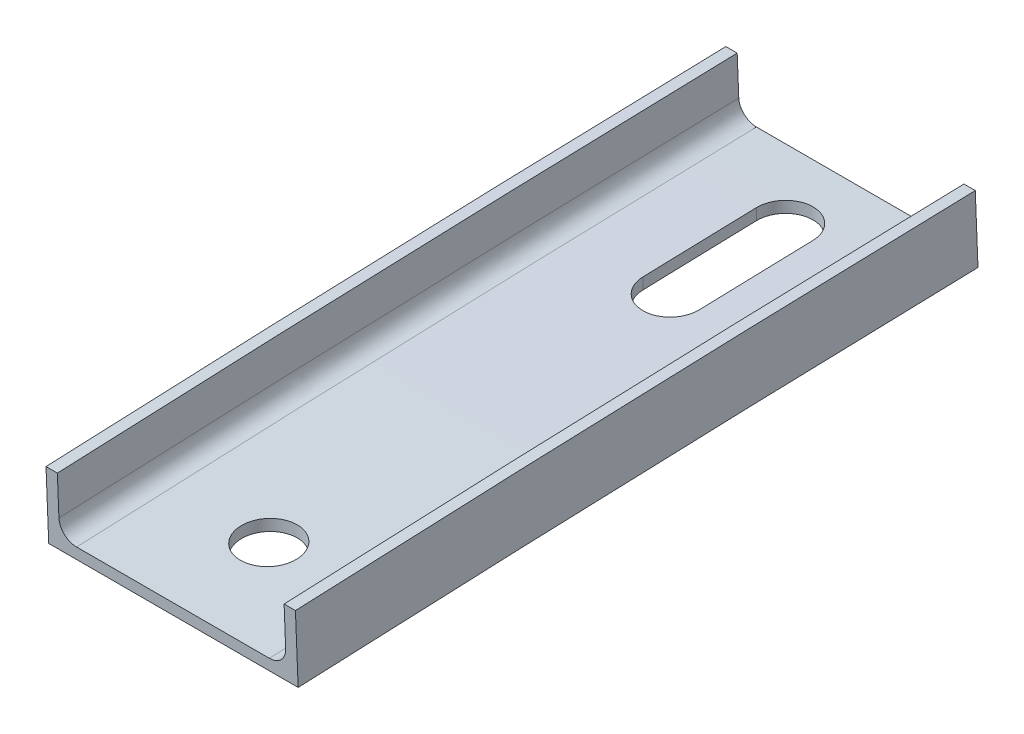
SolidWorks part; units mm, degrees
ref_plane "Front Plane" through (0, 0, 0) normal (0, 0, 1) x (1, 0, 0)
ref_plane "Top Plane" through (0, 0, 0) normal (0, 1, 0) x (1, 0, 0)
ref_plane "Right Plane" through (0, 0, 0) normal (1, 0, 0) x (0, 0, -1)
sketch "Sketch1" plane through (0, 0, 0) normal (0, 0, 1) x (1, 0, 0)
  line L0 (-17, 0) -> (17, 0)
  line L1 (-20, 3) -> (-20, 10)
  line L2 (-20, 10) -> (-22, 10)
  line L3 (-22, 10) -> (-22, -2)
  line L4 (-22, -2) -> (22, -2)
  line L5 (22, -2) -> (22, 10)
  line L6 (22, 10) -> (20, 10)
  line L7 (20, 10) -> (20, 3)
  arc A0 (17, 0) -> (20, 3) centre (17, 3) ccw
  arc A1 (-17, 0) -> (-20, 3) centre (-17, 3) cw
  point P4 (0, 0)
  point P12 (20, 0)
  point P15 (-20, 0)
  dimension "D4" = 3
  dimension "D1" = 2
  dimension "D2" = 2
  dimension "D3" = 40
  dimension "D5" = 10
sketch "Sketch3" plane through (0, 0, 0) normal (1, 0, 0) x (0, 0, -1)
  line L0 (-240, -6) -> (300, -6) construction
  arc A0 (-240, -6) -> (300, -6) centre (30, -6003) cw
  dimension "D1" = 540
  dimension "D2" = 6
  dimension "D3" = 300
sweep "Sweep1" add profiles "Sketch1" path "Sketch3"
sketch "Sketch4" plane through (0, 0, 0) normal (0, 1, 0) x (1, 0, 0)
  line L0 (0, 256.9001) -> (0, 276.9001) construction
  line L1 (-5, 256.9001) -> (-5, 276.9001)
  line L2 (5, 256.9001) -> (5, 276.9001)
  line L3 (0, 87.9001) -> (0, 107.9001) construction
  line L4 (-5, 87.9001) -> (-5, 107.9001)
  line L5 (5, 87.9001) -> (5, 107.9001)
  line L6 (0, -72.0999) -> (0, -52.0999) construction
  line L9 (0, 7.9001) -> (0, 27.9001) construction
  line L10 (-5, 7.9001) -> (-5, 27.9001)
  line L11 (5, 7.9001) -> (5, 27.9001)
  line L12 (-5, -72.0999) -> (-5, -52.0999)
  line L13 (5, -72.0999) -> (5, -52.0999)
  line L14 (-22, 299.9001) -> (22, 299.9001) construction
  line L15 (0, -152.0999) -> (0, -132.0999) construction
  line L16 (-5, -152.0999) -> (-5, -132.0999)
  line L17 (5, -152.0999) -> (5, -132.0999)
  arc A0 (-5, 256.9001) -> (5, 256.9001) centre (0, 256.9001) ccw
  arc A1 (5, 276.9001) -> (-5, 276.9001) centre (0, 276.9001) ccw
  arc A2 (-5, 87.9001) -> (5, 87.9001) centre (0, 87.9001) ccw
  arc A3 (5, 107.9001) -> (-5, 107.9001) centre (0, 107.9001) ccw
  arc A6 (-5, 7.9001) -> (5, 7.9001) centre (0, 7.9001) ccw
  arc A7 (5, 27.9001) -> (-5, 27.9001) centre (0, 27.9001) ccw
  arc A8 (-5, -72.0999) -> (5, -72.0999) centre (0, -72.0999) ccw
  arc A9 (5, -52.0999) -> (-5, -52.0999) centre (0, -52.0999) ccw
  arc A10 (-5, -152.0999) -> (5, -152.0999) centre (0, -152.0999) ccw
  arc A11 (5, -132.0999) -> (-5, -132.0999) centre (0, -132.0999) ccw
  circle A12 centre (0, 197.9001) radius 5
  circle A13 centre (0, -223.0999) radius 5
  point P3 (0, 266.9001)
  point P10 (0, 97.9001)
  point P17 (0, -62.0999)
  point P24 (0, 17.9001)
  point P33 (0, -142.0999)
  dimension "D1" = 5
  dimension "D3" = 33
  dimension "D9" = 10
  dimension "D10" = 10
  dimension "D2" = 20
  dimension "D4" = 202
  dimension "D5" = 282
  dimension "D6" = 362
  dimension "D7" = 442
  dimension "D8" = 102
  dimension "D11" = 523
extrude "Various mounting points" cut sketch "Sketch4" against normal through all both and the other way through all
ref_plane "Plane1" through (0, -4.8, 119.952) normal (0, -0.04, 0.9992) x (1, 0, 0)
sketch "Sketch5" plane through (0, -4.8, 119.952) normal (0, -0.04, 0.9992) x (1, 0, 0)
  line L1 (-81.6676, 40.1093) -> (60.3752, 40.1093)
  line L2 (-81.6676, 40.1093) -> (-81.6676, -52.7648)
  line L3 (-81.6676, -52.7648) -> (60.3752, -52.7648)
  line L4 (60.3752, 40.1093) -> (60.3752, -52.7648)
  point P4 (60.3752, -52.7648)
  point P5 (-81.6676, 40.1093)
extrude "Cut-Extrude1" cut sketch "Sketch5" against normal through all
